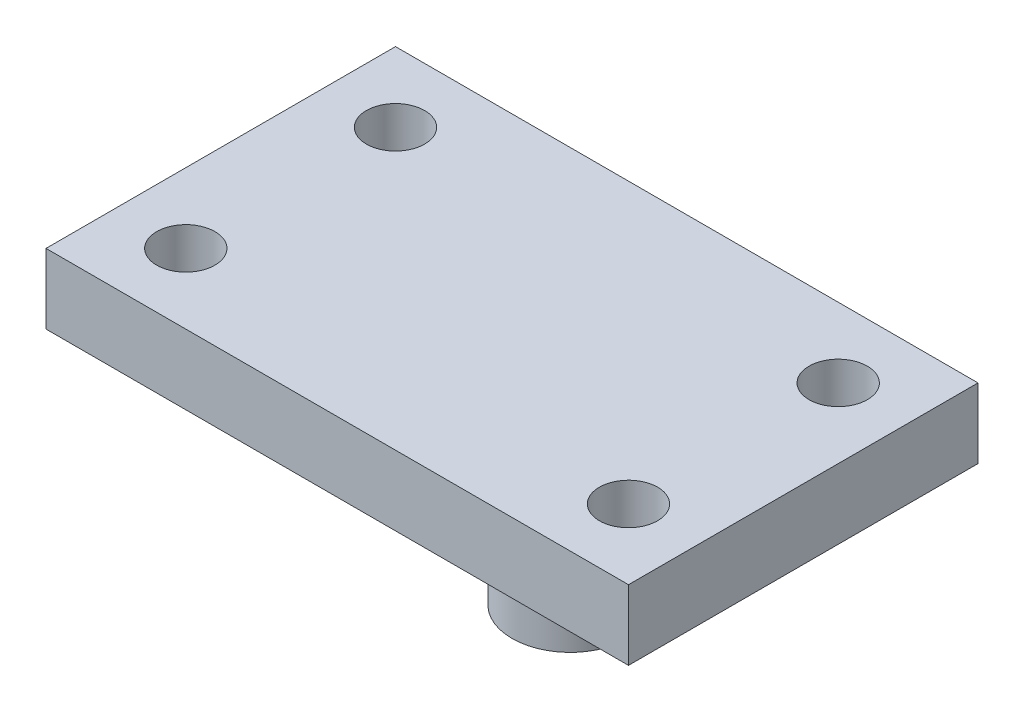
SolidWorks part; units mm, degrees
ref_plane "Front Plane" through (0, 0, 0) normal (0, 0, 1) x (1, 0, 0)
ref_plane "Top Plane" through (0, 0, 0) normal (0, 1, 0) x (1, 0, 0)
ref_plane "Right Plane" through (0, 0, 0) normal (1, 0, 0) x (0, 0, -1)
sketch "Sketch2" plane through (0, 0, 0) normal (0, 1, 0) x (1, 0, 0)
  line L1 (-125, 75) -> (125, 75)
  line L2 (-125, 75) -> (-125, -75)
  line L3 (-125, -75) -> (125, -75)
  line L4 (125, 75) -> (125, -75)
  line L5 (-125, 75) -> (125, -75) construction
  line L6 (-125, -75) -> (125, 75) construction
  point P0 (0, 0)
  dimension "D1" = 150
  dimension "D2" = 250
extrude "Boss-Extrude1" add sketch "Sketch2" along normal mid plane 30
sketch "Sketch3" plane through (0, 15, 0) normal (0, 1, 0) x (1, 0, 0)
  line L0 (-125, -75) -> (125, -75) construction
  line L1 (-125, 75) -> (-125, -75) construction
  line L2 (0, 0) -> (0, 42.7072) construction
  circle A0 centre (-95, -45) radius 12.5
  circle A1 centre (-95, 45) radius 12.5
  circle A4 centre (95, -45) radius 12.5
  circle A5 centre (95, 45) radius 12.5
  dimension "D1" = 25
  dimension "D2" = 30
  dimension "D3" = 30
  dimension "D4" = 90
extrude "Cut-Extrude1" cut sketch "Sketch3" against normal through all
sketch "Sketch4" plane through (0, -15, 0) normal (0, -1, 0) x (1, 0, 0)
  line L0 (125, -75) -> (-125, -75) construction
  circle A0 centre (0, -25) radius 25
  point P2 (0, 0)
  dimension "D1" = 50
  dimension "D2" = 50
extrude "Boss-Extrude2" add sketch "Sketch4" along normal blind 90
